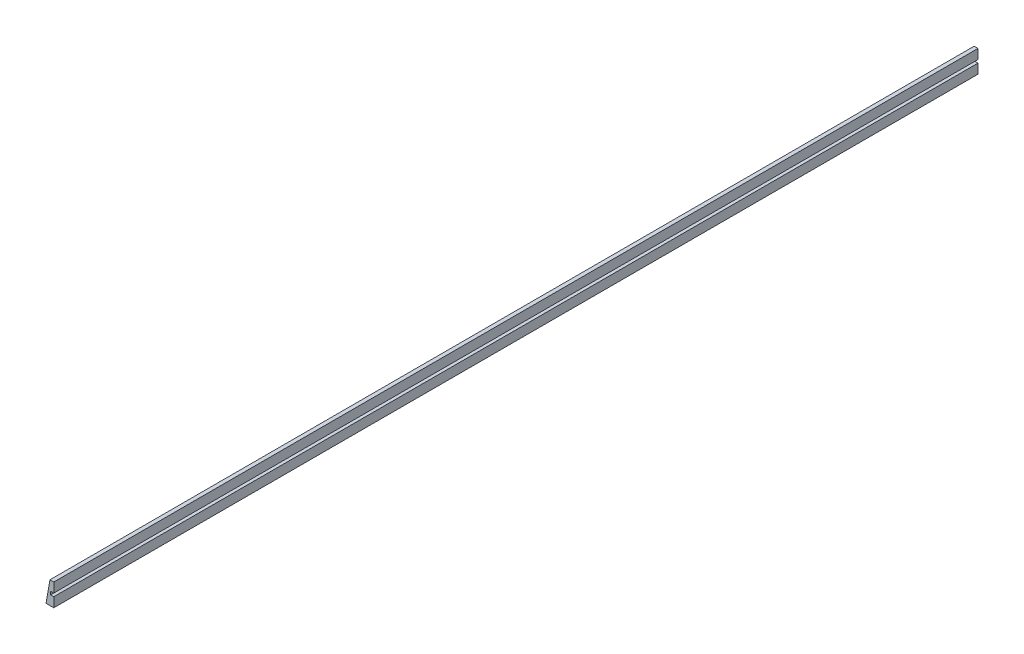
SolidWorks part; units mm, degrees
ref_plane "Front Plane" through (0, 0, 0) normal (0, 0, 1) x (1, 0, 0)
ref_plane "Top Plane" through (0, 0, 0) normal (0, 1, 0) x (1, 0, 0)
ref_plane "Right Plane" through (0, 0, 0) normal (1, 0, 0) x (0, 0, -1)
sketch "Sketch1" plane through (0, 0, 0) normal (0, 0, 1) x (1, 0, 0)
  line L0 (3.175, 2.54) -> (-1.905, 2.54)
  line L1 (-3.175, 18.415) -> (3.175, 18.415)
  line L2 (-3.175, 18.415) -> (-3.175, -18.415)
  line L3 (-3.175, -18.415) -> (3.175, -18.415)
  line L4 (3.175, 18.415) -> (3.175, 2.54)
  line L5 (-3.175, 18.415) -> (3.175, -18.415) construction
  line L6 (-3.175, -18.415) -> (3.175, 18.415) construction
  line L7 (-1.905, 2.54) -> (-1.905, -2.54)
  line L8 (-1.905, -2.54) -> (3.175, -2.54)
  line L9 (3.175, -2.54) -> (3.175, -18.415)
  line L10 (0, 0) -> (16.6384, 0) construction
  point P0 (0, 0)
  dimension "D1" = 36.83
  dimension "D2" = 6.35
  dimension "D3" = 5.08
  dimension "D4" = 5.08
extrude "Boss-Extrude1" add sketch "Sketch1" along normal mid plane 1524
sketch "Sketch2" plane through (0, 0, 0) normal (0, 0, 1) x (1, 0, 0)
  line L0 (-3.175, 18.415) -> (-3.175, -18.415)
  line L1 (-3.175, -18.415) -> (-9.6691, -18.415)
  line L2 (-9.6691, -18.415) -> (-3.175, 18.415)
  dimension "D1" = 10
extrude "Boss-Extrude2" add sketch "Sketch2" along normal up to surface and the other way up to surface
